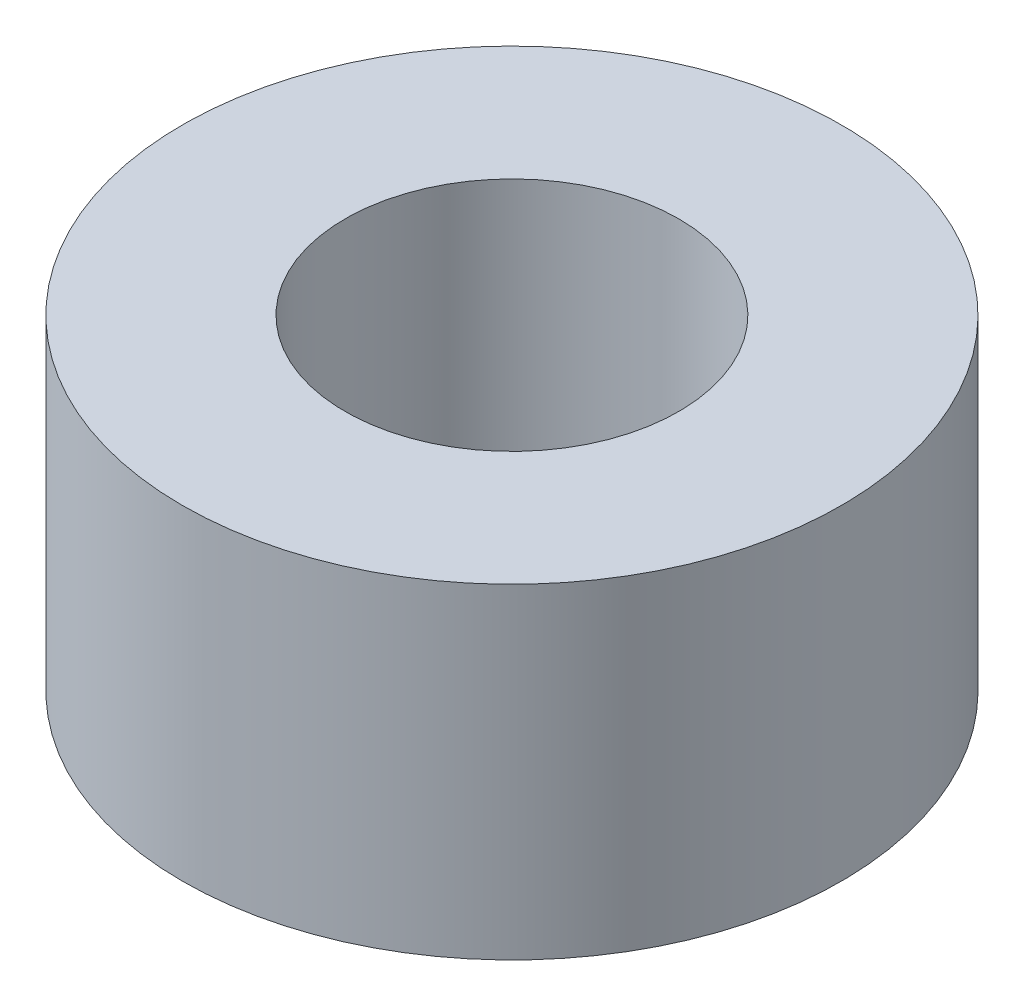
SolidWorks part; units mm, degrees
ref_plane "Ebene vorne" through (0, 0, 0) normal (0, 0, 1) x (1, 0, 0)
ref_plane "Ebene oben" through (0, 0, 0) normal (0, 1, 0) x (1, 0, 0)
ref_plane "Ebene rechts" through (0, 0, 0) normal (1, 0, 0) x (0, 0, -1)
sketch "Skizze2" plane through (0, 0, 0) normal (0, 1, 0) x (1, 0, 0)
  circle A0 centre (0, 0) radius 3.95
  dimension "D1" = 7.9
extrude "Aufsatz-Linear austragen1" add sketch "Skizze2" along normal blind 3.9
sketch "Skizze3" plane through (0, 0, 0) normal (0, -1, 0) x (1, 0, 0)
  circle A0 centre (0, 0) radius 2
  dimension "D1" = 4
extrude "Schnitt-Linear austragen1" cut sketch "Skizze3" against normal blind 3.9
